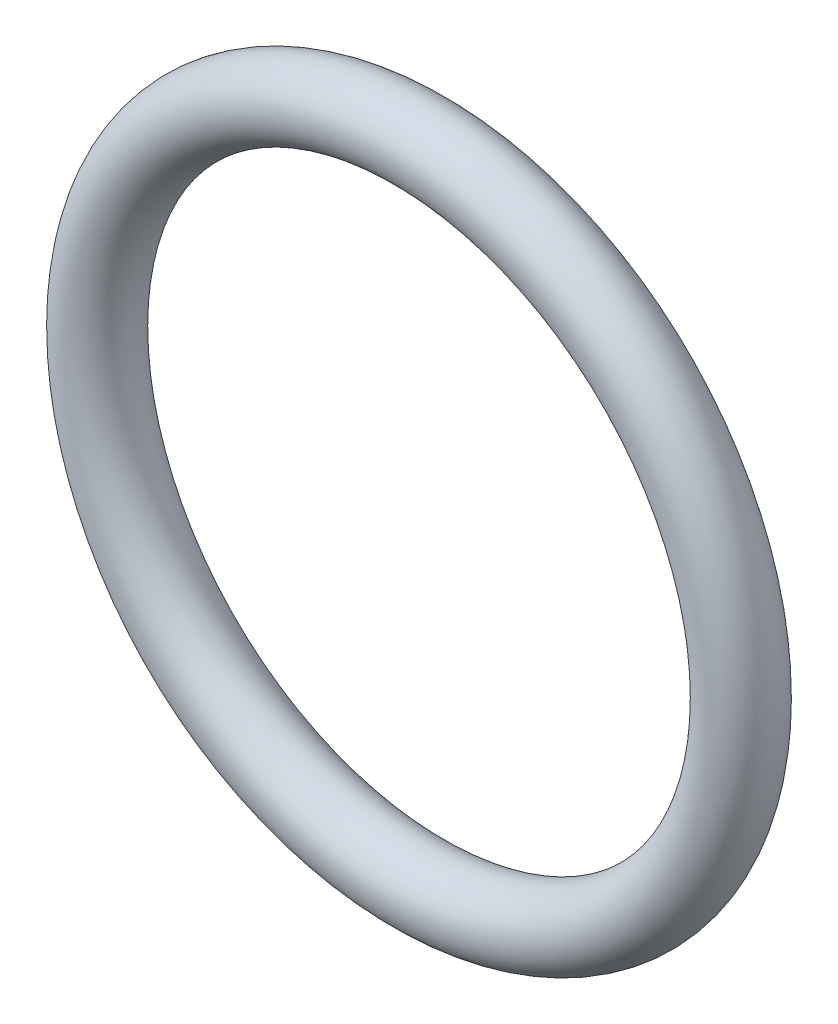
SolidWorks part; units mm, degrees
ref_plane "Front" through (0, 0, 0) normal (0, 0, 1) x (1, 0, 0)
ref_plane "Top" through (0, 0, 0) normal (0, 1, 0) x (1, 0, 0)
ref_plane "Right" through (0, 0, 0) normal (1, 0, 0) x (0, 0, -1)
sketch "Sketch1" plane through (0, 0, 0) normal (1, 0, 0) x (0, -1, 0)
  line L0 (0, -1.75) -> (0, 1.75) construction
  line L2 (-19.25, 0) -> (19.25, 0) construction
  line L3 (-14, 0) -> (14, 0) construction
  circle A0 centre (15.75, 0) radius 1.75
  point P9 (14, 0)
  point P10 (17.5, 0)
  point P13 (15.75, 1.75)
  point P14 (15.75, -1.75)
  dimension "Width" = 3.5
  dimension "ID" = 28
revolve "Revolve1" add sketch "Sketch1" angle 360 about L0
